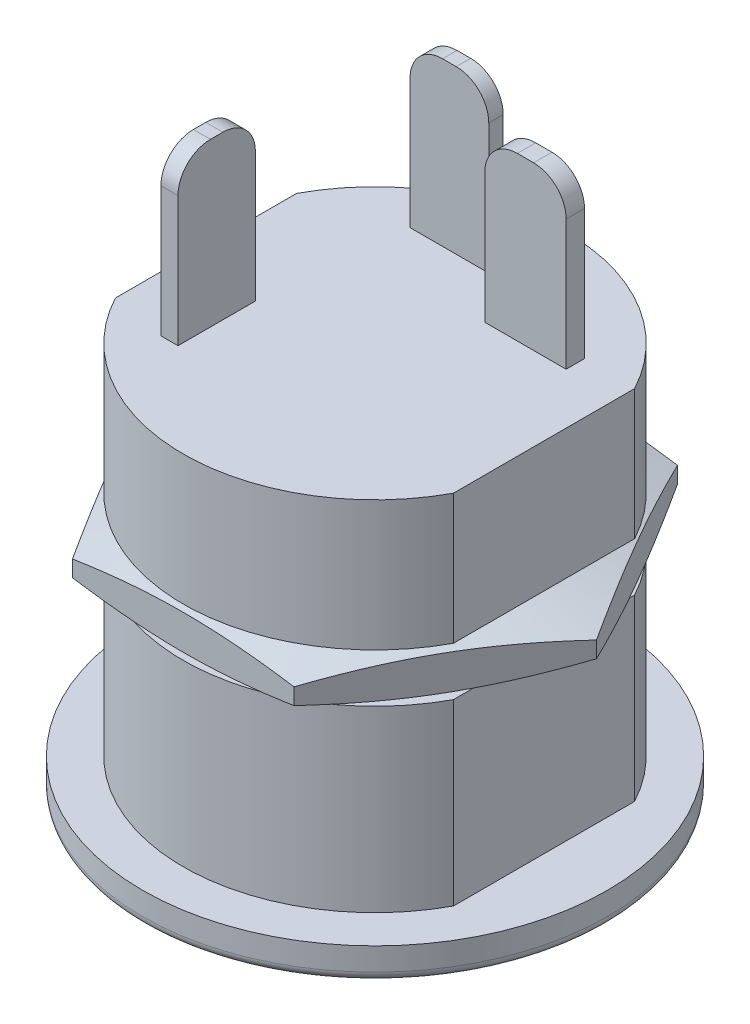
SolidWorks part; units mm, degrees
ref_plane "前视基准面" through (0, 0, 0) normal (0, 0, 1) x (1, 0, 0)
ref_plane "上视基准面" through (0, 0, 0) normal (0, 1, 0) x (1, 0, 0)
ref_plane "右视基准面" through (0, 0, 0) normal (1, 0, 0) x (0, 0, -1)
sketch "草图2" plane through (0, 0, 0) normal (0, 1, 0) x (1, 0, 0)
  circle A0 centre (0, 0) radius 5.9
  dimension "D1" = 11.8
extrude "凸台-拉伸1" add sketch "草图2" along normal blind 11
sketch "草图3" plane through (0, 0, 0) normal (0, -1, 0) x (1, 0, 0)
  circle A0 centre (0, 0) radius 7.15
  dimension "D1" = 14.3
extrude "凸台-拉伸2" add sketch "草图3" along normal blind 1
sketch "草图4" plane through (0, -1, 0) normal (0, -1, 0) x (1, 0, 0)
  circle A0 centre (0, 2.5) radius 3.1
  circle A1 centre (0, 0) radius 7.15 construction
  circle A2 centre (0, 2.5) radius 0.5
  dimension "D1" = 6.2
  dimension "D2" = 2.5
  dimension "D3" = 1
extrude "切除-拉伸1" cut sketch "草图4" against normal blind 5
fillet "圆角1" radius 0.3 1 edges at (0, -1, 2)
fillet "圆角2" radius 0.3 1 edges at (0, -1, -7.15)
sketch "草图5" plane through (0, 11, 0) normal (0, 1, 0) x (1, 0, 0)
  line L0 (-8.2, -10.5) -> (-8.2, 10.5)
  line L1 (5.2, -7.5) -> (-5.2, -7.5)
  line L2 (5.2, -7.5) -> (5.2, 7.5)
  line L3 (5.2, 7.5) -> (-5.2, 7.5)
  line L4 (-5.2, -7.5) -> (-5.2, 7.5)
  line L5 (5.2, -7.5) -> (-5.2, 7.5) construction
  line L6 (5.2, 7.5) -> (-5.2, -7.5) construction
  line L7 (8.2, 10.5) -> (-8.2, 10.5)
  line L8 (8.2, -10.5) -> (8.2, 10.5)
  line L9 (8.2, -10.5) -> (-8.2, -10.5)
  point P0 (0, 0)
  dimension "D1" = 10.4
  dimension "D2" = 15
  dimension "D3" = 3
extrude "切除-拉伸2" cut sketch "草图5" against normal up to surface (11 mm away) up to face at (0, 0, -5.9)
sketch "草图6" plane through (0, 11, 0) normal (0, 1, 0) x (1, 0, 0)
  line L1 (-2.5416, 4.0645) -> (-0.121, 4.0645)
  line L2 (-2.5416, 4.0645) -> (-2.5416, 3.6207)
  line L3 (-2.5416, 3.6207) -> (-0.121, 3.6207)
  line L4 (-0.121, 4.0645) -> (-0.121, 3.6207)
  line L5 (-2.5416, 4.0645) -> (-0.121, 3.6207) construction
  line L6 (-2.5416, 3.6207) -> (-0.121, 4.0645) construction
  line L7 (1.1296, 2.8139) -> (3.6308, 2.8139)
  line L8 (1.1296, 2.8139) -> (1.1296, 2.2491)
  line L9 (1.1296, 2.2491) -> (3.6308, 2.2491)
  line L10 (3.6308, 2.8139) -> (3.6308, 2.2491)
  line L11 (1.1296, 2.8139) -> (3.6308, 2.2491) construction
  line L12 (1.1296, 2.2491) -> (3.6308, 2.8139) construction
  line L13 (-3.4896, -0.7161) -> (-2.9652, -0.7161)
  line L14 (-3.4896, -0.7161) -> (-3.4896, -3.0963)
  line L15 (-3.4896, -3.0963) -> (-2.9652, -3.0963)
  line L16 (-2.9652, -0.7161) -> (-2.9652, -3.0963)
  line L17 (-3.4896, -0.7161) -> (-2.9652, -3.0963) construction
  line L18 (-3.4896, -3.0963) -> (-2.9652, -0.7161) construction
  point P0 (-1.3313, 3.8426)
  point P5 (2.3802, 2.5315)
  point P10 (-3.2274, -1.9062)
extrude "凸台-拉伸3" add sketch "草图6" along normal blind 5
fillet "圆角3" radius 1 6 edges at (-3.2274, 16, 3.0963) (-3.2274, 16, 0.7161) (-2.5416, 16, -3.8426) (1.1296, 16, -2.5315) (3.6308, 16, -2.5315) (-0.121, 16, -3.8426)
sketch "草图7" plane through (0, 11, 0) normal (0, 1, 0) x (1, 0, 0)
  line L0 (3.6308, 2.8139) -> (1.1296, 2.8139) construction
  line L1 (-3.4064, 5.9) -> (-6.8127, 0)
  line L2 (-6.8127, 0) -> (-3.4064, -5.9)
  line L3 (-3.4064, -5.9) -> (3.4064, -5.9)
  line L4 (3.4064, -5.9) -> (6.8127, 0)
  line L5 (6.8127, 0) -> (3.4064, 5.9)
  line L6 (3.4064, 5.9) -> (-3.4064, 5.9)
  circle A0 centre (0, 0) radius 5.9 construction
  arc A1 (5.2, 2.7875) -> (-5.2, 2.7875) centre (0, 0) ccw construction
extrude "凸台-拉伸4" add sketch "草图7" against normal blind 1.5 from offset 4 offset against normal yes
sketch "草图8" plane through (0, 0, 0) normal (0, 0, 1) x (1, 0, 0)
  line L0 (-6.8127, 7) -> (-6.8127, 6.5)
  line L1 (-6.8127, 5.5) -> (-6.8127, 7) construction
  line L2 (-6.8127, 6.5) -> (-5.2, 7)
  line L3 (-5.2, 7) -> (-6.8127, 7)
  line L4 (-6.8127, 7) -> (-5.1095, 7) construction
  line L5 (-6.8127, 6.25) -> (-5.0637, 6.25) construction
  line L6 (-5.2, 5.5) -> (-6.8127, 5.5)
  line L7 (-6.8127, 6) -> (-5.2, 5.5)
  line L8 (-6.8127, 5.5) -> (-6.8127, 6)
  dimension "D1" = 0.5
ref_axis "基准轴1" through (0, 11, 0) along (0, -1, 0)
revolve "切除-旋转1" cut sketch "草图8" angle 360 about axis through (0, 11, 0) along (0, -1, 0)
ref_point "点1"
ref_point "点5"
